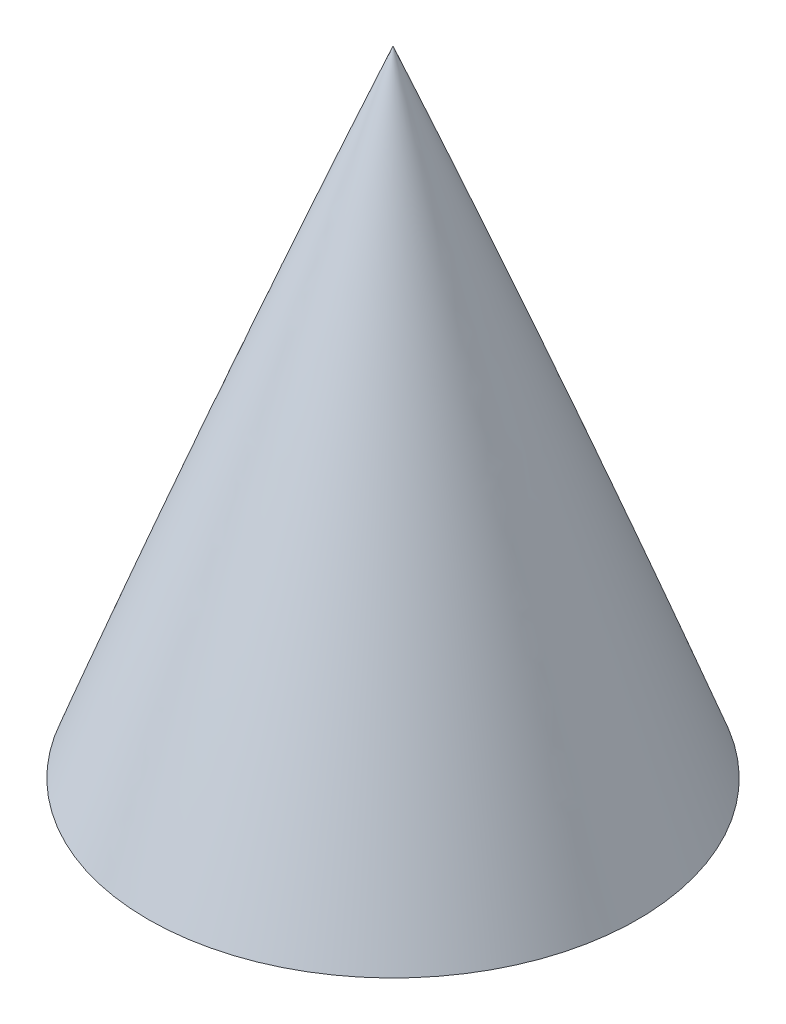
SolidWorks part; units mm, degrees
other "Markup1"
sketch "Sketch4" plane through (78.16, -154.2442, 78.16) normal (0.9651, -0.1718, 0.1975) x (-0.1686, -0.9851, -0.0334)
material "1060 Alloy"
ref_plane "Front Plane" through (0, 0, 0) normal (0, 0, 1) x (1, 0, 0)
ref_plane "Top Plane" through (0, 0, 0) normal (0, 1, 0) x (1, 0, 0)
ref_plane "Right Plane" through (0, 0, 0) normal (1, 0, 0) x (0, 0, -1)
sketch "Sketch1" plane through (0, 0, 0) normal (0, 0, 1) x (1, 0, 0)
  line L3 (0, 0) -> (0, 398.8705) construction
  line L6 (0, 400) -> (0, 401.8534)
  line L8 (78.2, 0) -> (76.2, 0)
  line L9 (0, 400) -> (0, 396.4892)
  line L10 (76.2, 0) -> (-993.4203, 0) construction
  line L11 (0, 411.0234) -> (0, 614.1078) construction
  arc A0 (76.2, 0) -> (0, 396.4892) centre (-993.4203, 0) ccw
  arc A1 (78.2, 0) -> (0, 401.8534) centre (-993.4203, 0) ccw
  circle A2 centre (-993.4203, 0) radius 1069.6203 construction
  circle A3 centre (-993.4203, 0) radius 1071.6203 construction
  point P11 (0, 400)
  dimension "D1" = 400
  dimension "D2" = 3.5108
  dimension "D3" = 2
  dimension "D4" = 76.2
revolve "Revolve3" add sketch "Sketch1" angle 360 about L6
sketch "Sketch2" plane through (0, 0, 0) normal (0, 1, 0) x (1, 0, 0)
  circle A3 centre (0, 0) radius 76.2 construction
  circle A4 centre (0, 0) radius 76.2
  circle A5 centre (0, 0) radius 74.2
  dimension "D1" = 2
extrude "Boss-Extrude1" add sketch "Sketch2" against normal blind 152.4 and the other way blind 10
ref_plane "Plane2" through (0, 400, 0) normal (0, -1, 0) x (-1, 0, 0)
ref_plane "Plane4" through (0, 370, 0) normal (0, -1, 0) x (-1, 0, 0)
sketch "Sketch6" plane through (0, 370, 0) normal (0, -1, 0) x (-1, 0, 0)
  circle A0 centre (0, 0) radius 147.184
extrude "Cut-Extrude1" cut sketch "Sketch6" along normal blind 1000 contours A0
